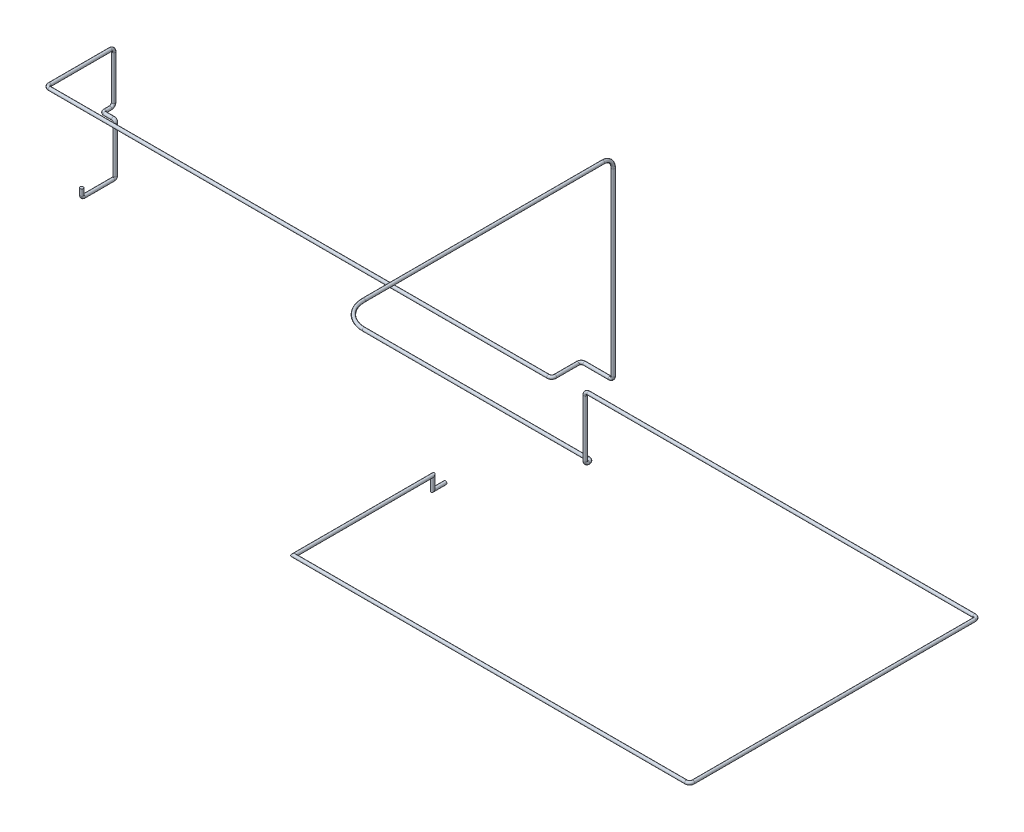
SolidWorks part; units mm, degrees
ref_plane "Alzado" through (0, 0, 0) normal (0, 0, 1) x (1, 0, 0)
ref_plane "Planta" through (0, 0, 0) normal (0, 1, 0) x (1, 0, 0)
ref_plane "Vista lateral" through (0, 0, 0) normal (1, 0, 0) x (0, 0, -1)
sketch "Croquis1" plane through (0, 0, 0) normal (0, 0, 1) x (1, 0, 0)
  circle A0 centre (0, 0) radius 19.05
  dimension "D1" = 38.1
extrude "Saliente-Extruir1" add sketch "Croquis1" against normal blind 10
sketch3d "Croquis3D1"
  line L0 (0, 0, -10) -> (0, 0, -30)
  line L1 (0, 0, -10) -> (0, 0, 0) construction
  line L2 (0, 40, -70) -> (0, 560, -70)
  line L3 (0, 600, -30) -> (0, 600, 690)
  line L4 (40, 600, 730) -> (5960, 600, 730)
  line L5 (6000, 600, 690) -> (6000, 600, 420)
  line L6 (6040, 600, 380) -> (6340, 600, 380)
  line L7 (6380, 640, 380) -> (6380, 2780, 380)
  line L8 (6380, 2900, 500) -> (6380, 2900, 3340)
  line L9 (6680, 2900, 3640) -> (9345, 2900, 3640)
  line L10 (9380, 2900, 3675) -> (9380, 2900, 3677)
  line L11 (9380, 2935, 3712) -> (9380, 3610, 3712)
  line L12 (9420, 3650, 3712) -> (14000, 3650, 3712)
  line L13 (14040, 3650, 3752) -> (14040, 3650, 7092)
  line L14 (14000, 3650, 7132) -> (9340, 3650, 7132)
  line L15 (9340, 3650, 7132) -> (9340, 3650, 5482)
  line L16 (9340, 3650, 5482) -> (9340, 3500, 5482)
  line L17 (9340, 3500, 5482) -> (9340, 3500, 5332)
  arc A0 (6380, 2900, 3340) -> (6680, 2900, 3640) centre (6680, 2900, 3340) ccw
  arc A1 (9380, 2900, 3677) -> (9380, 2935, 3712) centre (9380, 2935, 3677) ccw
  arc A2 (9345, 2900, 3640) -> (9380, 2900, 3675) centre (9345, 2900, 3675) ccw
  arc A3 (6380, 2780, 380) -> (6380, 2900, 500) centre (6380, 2780, 500) ccw
  arc A4 (6340, 600, 380) -> (6380, 640, 380) centre (6340, 640, 380) ccw
  arc A5 (6000, 600, 420) -> (6040, 600, 380) centre (6040, 600, 420) ccw
  arc A6 (5960, 600, 730) -> (6000, 600, 690) centre (5960, 600, 690) ccw
  arc A7 (0, 600, 690) -> (40, 600, 730) centre (40, 600, 690) ccw
  arc A8 (0, 560, -70) -> (0, 600, -30) centre (0, 560, -30) ccw
  arc A9 (0, 0, -30) -> (0, 40, -70) centre (0, 40, -30) ccw
  arc A10 (14040, 3650, 7092) -> (14000, 3650, 7132) centre (14000, 3650, 7092) ccw
  arc A11 (14000, 3650, 3712) -> (14040, 3650, 3752) centre (14000, 3650, 3752) ccw
  arc A12 (9380, 3610, 3712) -> (9420, 3650, 3712) centre (9420, 3610, 3712) ccw
  point P19 (6380, 2900, 3640)
  point P20 (6680, 3200, 3340)
  point P23 (9380, 2900, 3712)
  point P24 (9345, 2935, 3677)
  point P27 (9380, 2900, 3640)
  point P28 (9345, 2865, 3675)
  point P31 (6380, 2900, 380)
  point P32 (6500, 2780, 500)
  point P35 (6380, 600, 380)
  point P36 (6340, 640, 420)
  point P39 (6000, 600, 380)
  point P40 (6040, 560, 420)
  point P43 (6000, 600, 730)
  point P44 (5960, 640, 690)
  point P47 (0, 600, 730)
  point P48 (40, 640, 690)
  point P51 (0, 600, -70)
  point P52 (40, 560, -30)
  point P55 (0, 0, -70)
  point P56 (40, 40, -30)
  point P59 (14040, 3650, 7132)
  point P60 (14000, 3610, 7092)
  point P63 (14040, 3650, 3712)
  point P64 (14000, 3610, 3752)
  point P67 (9380, 3650, 3712)
  point P68 (9420, 3610, 3672)
  dimension "D15" = 300
  dimension "D16" = 35
  dimension "D17" = 120
  dimension "D18" = 40
  dimension "D19" = 40
  dimension "D1" = 60
  dimension "D2" = 600
  dimension "D3" = 800
  dimension "D4" = 6000
  dimension "D5" = 350
  dimension "D6" = 380
  dimension "D7" = 2300
  dimension "D8" = 3260
  dimension "D9" = 3000
  dimension "D10" = 72
  dimension "D12" = 4660
  dimension "D11" = 750
  dimension "D13" = 3420
  dimension "D14" = 4700
  dimension "D20" = 1650
  dimension "D21" = 150
  dimension "D22" = 150
sketch "Croquis2" plane through (0, 0, -10) normal (0, 0, -1) x (-1, 0, 0)
  circle A0 centre (0, 0) radius 19.05
  dimension "D1" = 38.1
sweep "Barrer1" add profiles "Croquis2" path "Croquis3D1"
sketch3d "Croquis3D2"
  line L0 (0, 0, 0) -> (0, 0, 35)
  line L1 (25, 0, 60) -> (125, 0, 60)
  line L2 (150, -25, 60) -> (150, -575, 60)
  line L3 (150, -600, 85) -> (150, -600, 435)
  line L4 (150, -575, 460) -> (150, -500, 460)
  arc A0 (150, -600, 435) -> (150, -575, 460) centre (150, -575, 435) ccw
  arc A1 (150, -575, 60) -> (150, -600, 85) centre (150, -575, 85) ccw
  arc A2 (125, 0, 60) -> (150, -25, 60) centre (125, -25, 60) ccw
  arc A3 (0, 0, 35) -> (25, 0, 60) centre (25, 0, 35) ccw
  point P9 (150, -600, 460)
  point P10 (125, -575, 435)
  point P13 (150, -600, 60)
  point P14 (125, -575, 85)
  point P17 (150, 0, 60)
  point P18 (125, -25, 35)
  point P21 (0, 0, 60)
  point P22 (25, 25, 35)
  dimension "D6" = 25
  dimension "D1" = 60
  dimension "D2" = 150
  dimension "D3" = 600
  dimension "D4" = 400
  dimension "D5" = 100
sketch "Croquis3" plane through (0, 0, 0) normal (0, 0, 1) x (1, 0, 0)
  circle A0 centre (0, 0) radius 19.05
sweep "Barrer2" add profiles "Croquis3" path "Croquis3D2"
